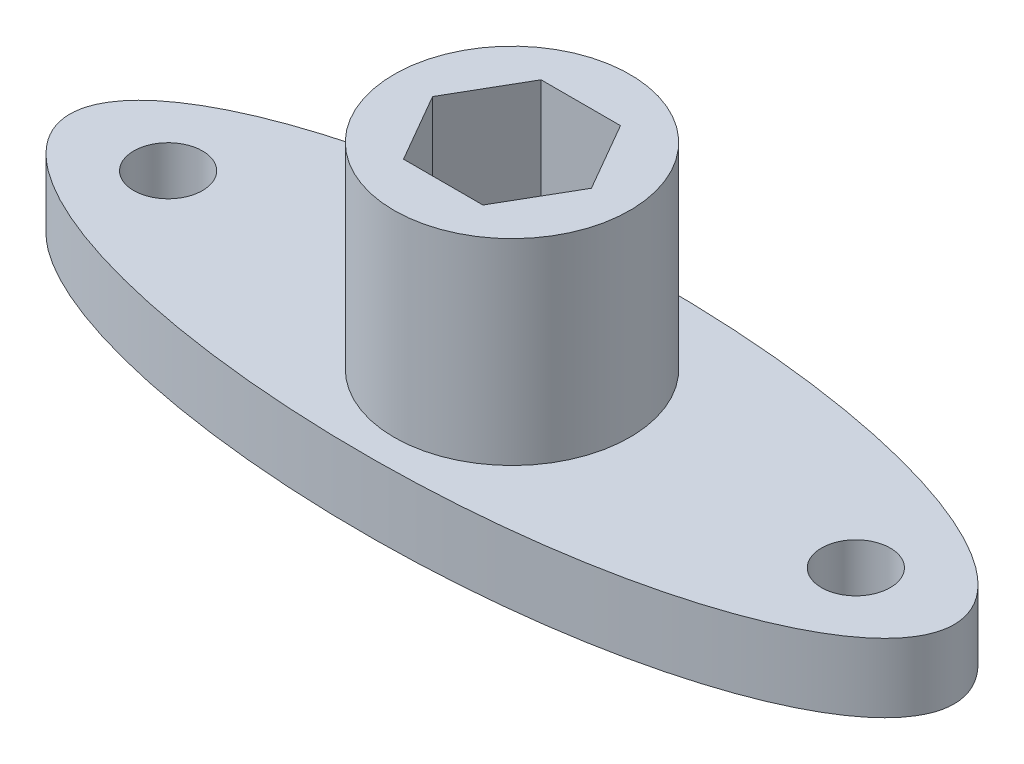
SolidWorks part; units mm, degrees
ref_plane "Front Plane" through (0, 0, 0) normal (0, 0, 1) x (1, 0, 0)
ref_plane "Top Plane" through (0, 0, 0) normal (0, 1, 0) x (1, 0, 0)
ref_plane "Right Plane" through (0, 0, 0) normal (1, 0, 0) x (0, 0, -1)
sketch "Sketch2" plane through (0, 0, 0) normal (0, 1, 0) x (1, 0, 0)
  line L0 (0, -427.4227) -> (0, 20943.7134) construction
  line L1 (-427.4227, 0) -> (20943.7134, 0) construction
  circle A2 centre (17.5, 0) radius 1.75
  circle A3 centre (-17.5, 0) radius 1.75
  ellipse E0 centre (0, 0) end of major axis (22.5, 0) minor radius 7.5
  dimension "D5" = 3.5
  dimension "D1" = 45
  dimension "D2" = 15
  dimension "D6" = 5
extrude "Boss-Extrude3" add sketch "Sketch2" along normal blind 3.5
sketch "Sketch3" plane through (0, 3.5, 0) normal (0, 1, 0) x (1, 0, 0)
  circle A0 centre (0, 0) radius 6
  dimension "D1" = 12
extrude "Boss-Extrude4" add sketch "Sketch3" along normal blind 10
sketch "Sketch4" plane through (0, 13.5, 0) normal (0, 1, 0) x (1, 0, 0)
  line L1 (2.0207, -3.5) -> (4.0415, 0)
  line L2 (4.0415, 0) -> (2.0207, 3.5)
  line L3 (2.0207, 3.5) -> (-2.0207, 3.5)
  line L4 (-2.0207, 3.5) -> (-4.0415, 0)
  line L5 (-4.0415, 0) -> (-2.0207, -3.5)
  line L6 (-2.0207, -3.5) -> (2.0207, -3.5)
  circle A0 centre (0, 0) radius 3.5 construction
  dimension "D1" = 7
extrude "Cut-Extrude1" cut sketch "Sketch4" against normal blind 6.5
